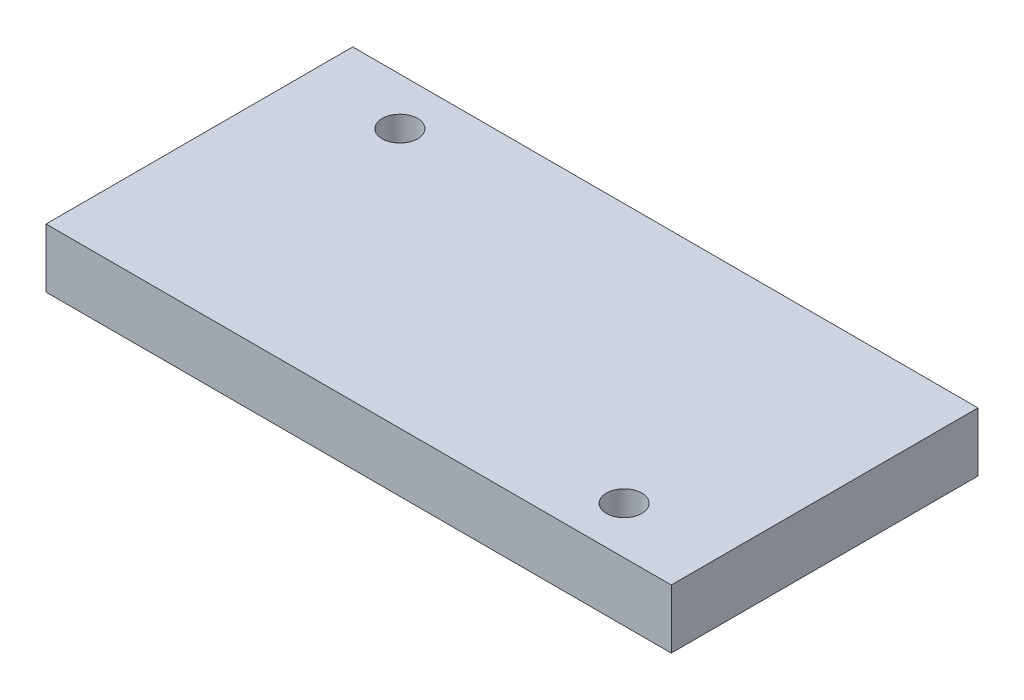
SolidWorks part; units mm, degrees
ref_plane "Piano frontale" through (0, 0, 0) normal (0, 0, 1) x (1, 0, 0)
ref_plane "Piano superiore" through (0, 0, 0) normal (0, 1, 0) x (1, 0, 0)
ref_plane "Piano destro" through (0, 0, 0) normal (1, 0, 0) x (0, 0, -1)
sketch "Schizzo1" plane through (0, 0, 0) normal (0, 1, 0) x (1, 0, 0)
  line L1 (-26.5, -13) -> (26.5, -13)
  line L2 (-26.5, -13) -> (-26.5, 13)
  line L3 (-26.5, 13) -> (26.5, 13)
  line L4 (26.5, -13) -> (26.5, 13)
  line L5 (-26.5, -13) -> (26.5, 13) construction
  line L6 (-26.5, 13) -> (26.5, -13) construction
  point P0 (0, 0)
  dimension "D1" = 53
  dimension "D2" = 26
extrude "Estrusione-Estrusione1" add sketch "Schizzo1" along normal blind 5
sketch "Schizzo2" plane through (0, 5, 0) normal (0, 1, 0) x (1, 0, 0)
  line L0 (-26.5, 13) -> (-26.5, -13) construction
  line L1 (26.5, 13) -> (-26.5, 13) construction
  line L2 (26.5, -13) -> (26.5, 13) construction
  line L3 (-26.5, -13) -> (26.5, -13) construction
  circle A0 centre (-18.5, 9) radius 1.5
  circle A1 centre (18.5, -9) radius 1.5
  dimension "D3" = 3
  dimension "D5" = 3
  dimension "D1" = 8
  dimension "D2" = 4
  dimension "D4" = 8
  dimension "D6" = 4
extrude "Taglio-Estrusione1" cut sketch "Schizzo2" against normal blind 13
